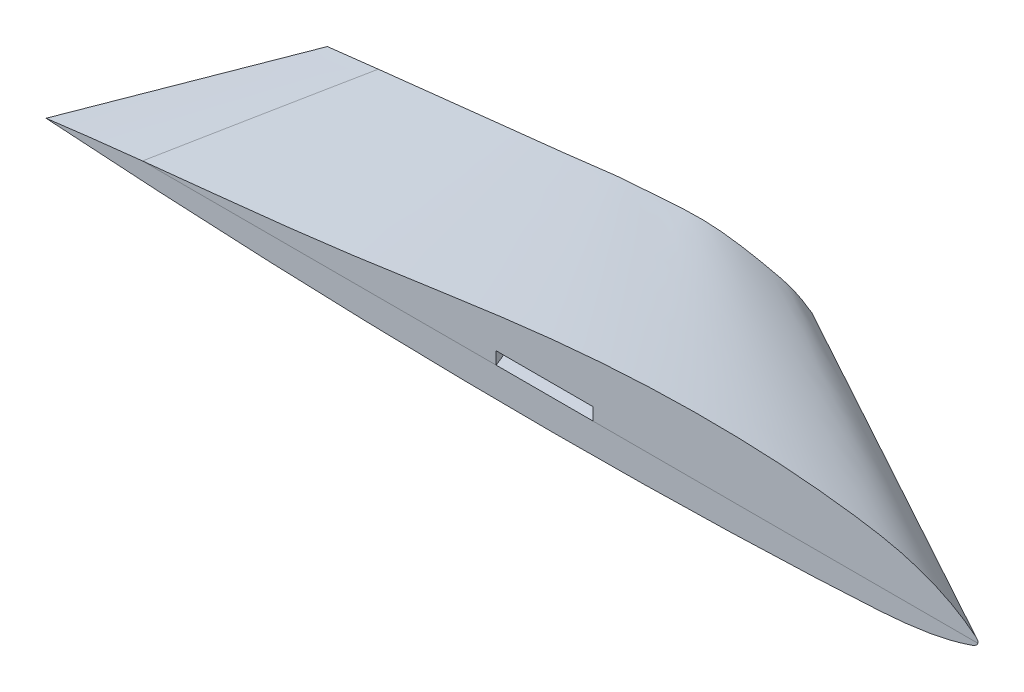
SolidWorks part; units mm, degrees
material "EPS 1.5lb"
ref_plane "Front Plane" through (0, 0, 0) normal (0, 0, 1) x (1, 0, 0)
ref_plane "Top Plane" through (0, 0, 0) normal (0, 1, 0) x (1, 0, 0)
ref_plane "Right Plane" through (0, 0, 0) normal (1, 0, 0) x (0, 0, -1)
sketch "Sketch1" plane through (0, 0, 0) normal (0, 0, 1) x (1, 0, 0)
  spline S3 degree 3 poles (-353.0971, 3.7664) (-263.6099, 15.4897) (-103.4056, 27.7025) (139.6254, 69.7319) (320.6009, 70.898) (447.0294, 49.1568) (484.462, 32.3978) (505.2254, 13.2914) knots 0 0 0 0 0.308402 0.542913 0.85017 0.887176 1 1 1 1
  spline S4 degree 3 poles (-353.0971, 3.7664) (-171.2042, -8.6227) (70.6812, -17.727) (367.6345, -8.5893) (467.935, -1.6347) (505.2254, 13.2914) knots 0 0 0 0 0.625313 0.861779 1 1 1 1
ref_plane "Plane1" through (0, 0, -180.975) normal (0, 0, 1) x (1, 0, 0)
sketch "Sketch2" plane through (0, 0, -180.975) normal (0, 0, 1) x (1, 0, 0)
  ellipse E1 centre (137.6249, -20.0426) end of major axis (189.6794, -20.0426) minor radius 48.2641 (175.2698, 13.2914) -> (153.373, 25.9598) ccw construction
  spline S0 degree 3 poles (-276.1301, 8.6931) (-231.4597, 13.8922) (-160.6069, 22.0458) (-55.2186, 32.8482) (-5.4847, 39.5878) (20.2948, 40.7341) (52.2153, 43.3112) (77.4334, 43.8548) (107.6579, 39.591) (131.1314, 34.7665) (149.4992, 30.2941) (163.4187, 23.0591) (171.5303, 16.9219) (175.2698, 13.2914) knots 0 0 0 0 0.247404 0.462109 0.504395 0.627983 0.653402 0.743134 0.818761 0.882434 0.92418 0.960505 1 1 1 1
  spline S4 degree 3 poles (-276.1301, 8.6931) (-174.261, 0.9112) (-23.6694, 0.6839) (127.5151, 0.6814) (175.2698, 13.2914) knots 0 0 0 0 0.676464 1 1 1 1
loft "Loft1" add profiles "Sketch1", "Sketch2"
fillet "Fillet1" radius 6.35 1 edges
ref_plane "Plane2" through (0, 19.812, 0) normal (0, 1, 0) x (1, 0, 0)
sketch "Sketch7" plane through (0, 19.812, 0) normal (0, 1, 0) x (1, 0, 0)
  line L0 (148.5529, 0) -> (75.4342, 180.975)
  line L1 (-13.4658, 180.975) -> (59.6529, 0)
  line L2 (59.6529, 0) -> (148.5529, 0)
  line L3 (75.4342, 180.975) -> (-13.4658, 180.975)
  line L5 (-44.6577, 180.975) -> (44.6577, 180.975) construction
  line L7 (-44.6562, 0) -> (44.6562, 0) construction
  dimension "D1" = 501.65
  dimension "D2" = 88.9
  dimension "D3" = 68
  dimension "D4" = 88.9
extrude "Cut-Extrude1" cut sketch "Sketch7" against normal mid plane 11.43
sketch "Sketch8" plane through (0, 19.812, 0) normal (0, 1, 0) x (1, 0, 0)
  line L0 (-276.1301, 180.975) -> (-353.0971, 0) construction
  line L2 (-328.3189, 58.2617) -> (-239.4979, 20.487)
  line L3 (-239.4979, 20.487) -> (-171.2438, 180.975)
  line L4 (-171.2438, 180.975) -> (-276.1301, 180.975)
  line L5 (167.9966, 180.975) -> (-276.1301, 180.975) construction
  line L6 (167.9966, 180.975) -> (-276.1301, 180.975) construction
  line L7 (-276.1301, 180.975) -> (-328.3189, 58.2617)
  dimension "D1" = 133.35
  dimension "D2" = 96.52
extrude "Cut-Extrude2" [suppressed] cut sketch "Sketch8" against normal through all and the other way through all
sketch "Sketch9" plane through (0, 0, 0) normal (0, 0, 1) x (1, 0, 0)
  line L0 (501.6041, 0) -> (501.407, 14.9983) construction
  line L1 (99.5364, 0) -> (-99.5364, 0) construction
  line L2 (501.407, 14.9983) -> (-353.0971, 3.7664) construction
  spline S0 degree 3 poles (495.958, 9.828) (496.8835, 10.1499) (497.7705, 10.5419) (499.008, 11.2994) (499.4048, 11.5805) (500.1496, 12.2315) (500.4885, 12.594) (500.9041, 13.2106) (501.0244, 13.4247) (501.2214, 13.8733) (501.2987, 14.1109) (501.3955, 14.5963) (501.415, 14.8413) (501.3938, 15.3365) (501.3526, 15.5828) (501.2176, 16.0565) (501.1224, 16.2887) (500.8939, 16.7255) (500.7606, 16.9316) (500.4639, 17.3241) (500.2996, 17.5112) (499.9516, 17.8629) (499.7676, 18.0283) (499.5755, 18.185) knots 0 0 0 0 0.25 0.25 0.375 0.375 0.5 0.5 0.5625 0.5625 0.625 0.625 0.6875 0.6875 0.75 0.75 0.8125 0.8125 0.875 0.875 0.9375 0.9375 1 1 1 1 construction
sketch "Sketch10" plane through (0, 0, -180.975) normal (0, 0, -1) x (-1, 0, 0)
  line L0 (-170.4193, 0) -> (-170.1582, 15.9838) construction
  line L1 (-170.1582, 15.9838) -> (276.1301, 8.6931) construction
  line L2 (99.5364, 0) -> (-99.5364, 0) construction
  spline S1 degree 3 poles (-167.9966, 19.4182) (-168.2414, 19.238) (-168.4753, 19.0462) (-168.9159, 18.6336) (-169.1233, 18.4121) (-169.4986, 17.9328) (-169.663, 17.6797) (-169.932, 17.1385) (-170.0362, 16.8477) (-170.1566, 16.2561) (-170.1738, 15.9468) (-170.1306, 15.4957) (-170.1051, 15.347) (-170.0331, 15.0527) (-169.9861, 14.9062) (-169.8194, 14.4828) (-169.6742, 14.2186) (-169.3313, 13.7181) (-169.1348, 13.4845) (-168.7149, 13.0536) (-168.4897, 12.8542) (-168.0156, 12.4801) (-167.766, 12.3054) (-167.003, 11.8211) (-166.4706, 11.5466) (-165.3734, 11.0635) (-164.8067, 10.855) (-163.6551, 10.494) (-163.0716, 10.3417) (-162.4816, 10.2129) knots 0 0 0 0 0.0625 0.0625 0.125 0.125 0.1875 0.1875 0.25 0.25 0.3125 0.3125 0.34375 0.34375 0.375 0.375 0.4375 0.4375 0.5 0.5 0.5625 0.5625 0.625 0.625 0.75 0.75 0.875 0.875 1 1 1 1 construction
ref_plane "Plane3" through (0, 14.097, 0) normal (0, 1, 0) x (1, 0, 0)
split "Split1" trim tools "Plane3" bodies to split 104 resulting bodies 107 108
